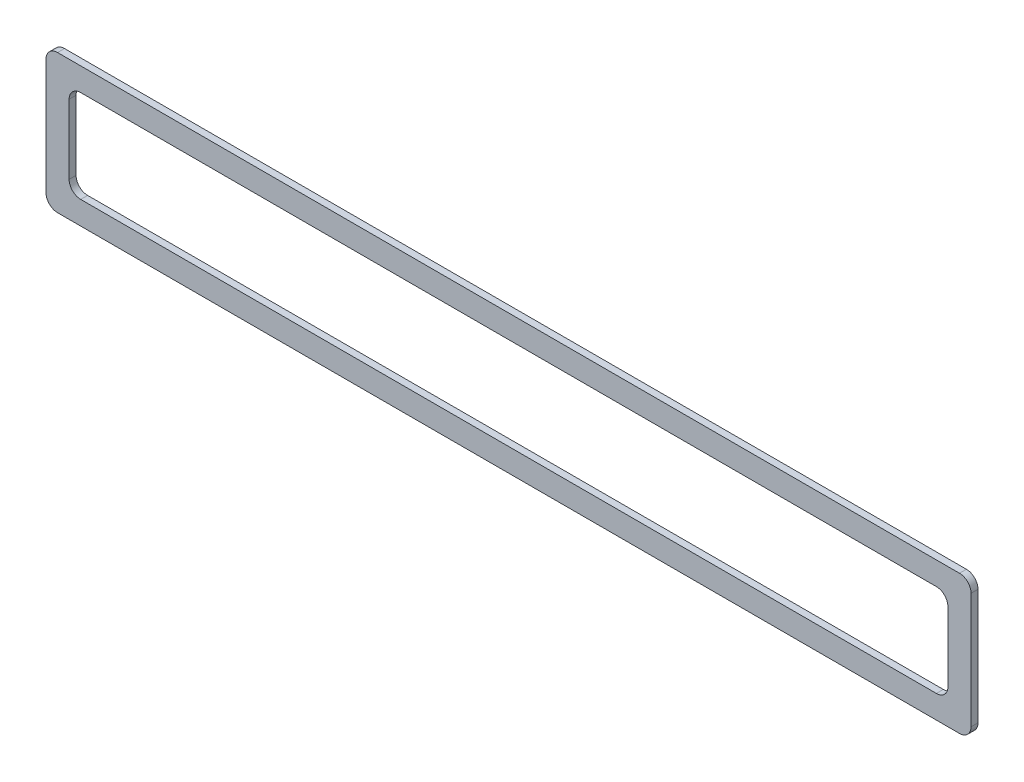
SolidWorks part; units mm, degrees
ref_plane "Front Plane" through (0, 0, 0) normal (0, 0, 1) x (1, 0, 0)
ref_plane "Top Plane" through (0, 0, 0) normal (0, 1, 0) x (1, 0, 0)
ref_plane "Right Plane" through (0, 0, 0) normal (1, 0, 0) x (0, 0, -1)
sketch "Sketch1" plane through (0, 0, 0) normal (0, 0, 1) x (1, 0, 0)
  line L1 (-185, -20) -> (185, -20)
  line L2 (-190, -15) -> (-190, 15)
  line L3 (-185, 20) -> (185, 20)
  line L4 (190, -15) -> (190, 15)
  line L5 (-190, -20) -> (190, 20) construction
  line L6 (-190, 20) -> (190, -20) construction
  line L7 (-195, -30) -> (195, -30)
  line L8 (-200, -25) -> (-200, 25)
  line L9 (-195, 30) -> (195, 30)
  line L10 (200, -25) -> (200, 25)
  line L11 (-200, -30) -> (200, 30) construction
  line L12 (-200, 30) -> (200, -30) construction
  arc A0 (-190, 15) -> (-185, 20) centre (-185, 15) cw
  arc A1 (-185, -20) -> (-190, -15) centre (-185, -15) cw
  arc A2 (185, -20) -> (190, -15) centre (185, -15) ccw
  arc A3 (185, 20) -> (190, 15) centre (185, 15) cw
  arc A4 (195, 30) -> (200, 25) centre (195, 25) cw
  arc A5 (195, -30) -> (200, -25) centre (195, -25) ccw
  arc A6 (-195, -30) -> (-200, -25) centre (-195, -25) cw
  arc A7 (-200, 25) -> (-195, 30) centre (-195, 25) cw
  point P0 (0, 0)
  point P18 (0, 0)
  dimension "D3" = 5
  dimension "D6" = 5
  dimension "D1" = 40
  dimension "D2" = 380
  dimension "D4" = 10
  dimension "D5" = 10
extrude "Extrude1" add sketch "Sketch1" along normal blind 3
